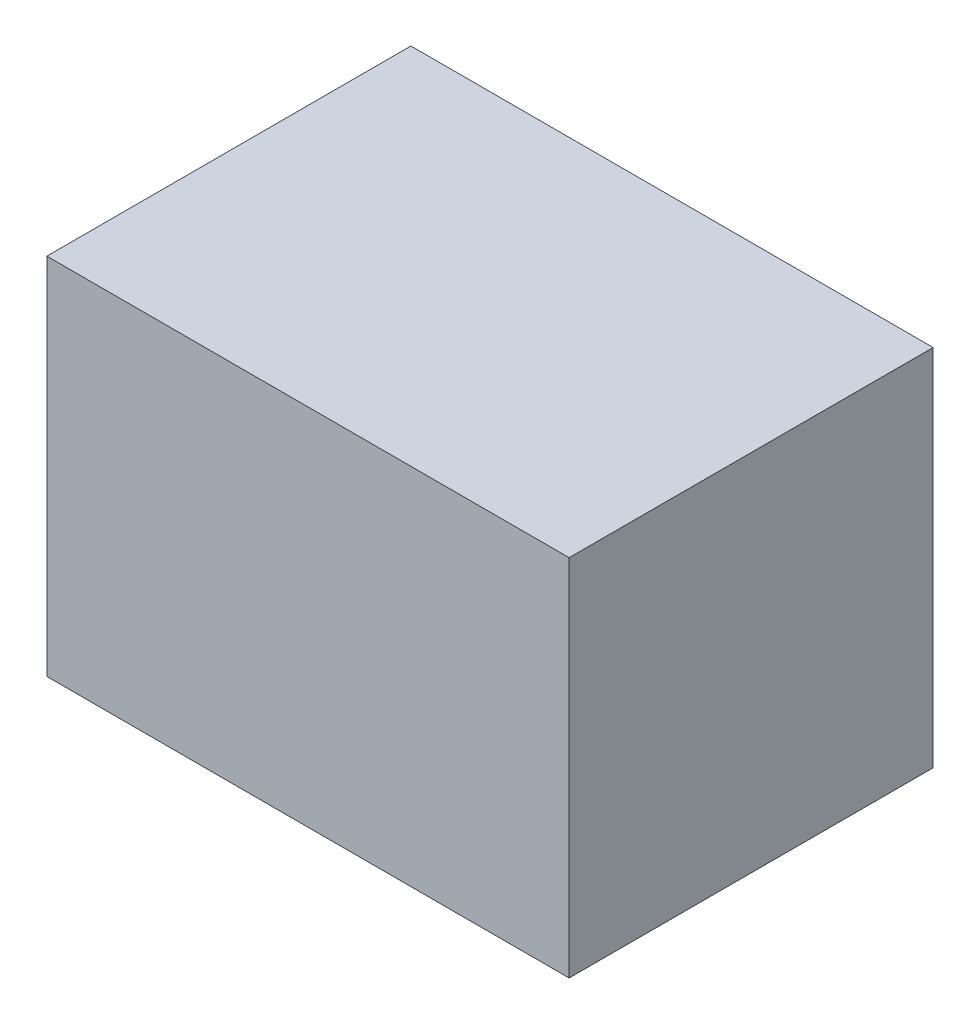
SolidWorks part; units mm, degrees
ref_plane "Front Plane" through (0, 0, 0) normal (0, 0, 1) x (1, 0, 0)
ref_plane "Top Plane" through (0, 0, 0) normal (0, 1, 0) x (1, 0, 0)
ref_plane "Right Plane" through (0, 0, 0) normal (1, 0, 0) x (0, 0, -1)
sketch "Sketch1" plane through (0, 0, 0) normal (0, 0, 1) x (1, 0, 0)
  line L1 (-159.7684, -131.3731) -> (-54.9934, -131.3731)
  line L2 (-159.7684, -131.3731) -> (-159.7684, -58.3481)
  line L3 (-159.7684, -58.3481) -> (-54.9934, -58.3481)
  line L4 (-54.9934, -131.3731) -> (-54.9934, -58.3481)
  line L5 (-159.7684, -131.3731) -> (-54.9934, -58.3481) construction
  line L6 (-159.7684, -58.3481) -> (-54.9934, -131.3731) construction
  point P0 (-107.3809, -94.8606)
  dimension "D1" = 73.025
  dimension "D2" = 104.775
extrude "Boss-Extrude1" add sketch "Sketch1" along normal blind 73.025
